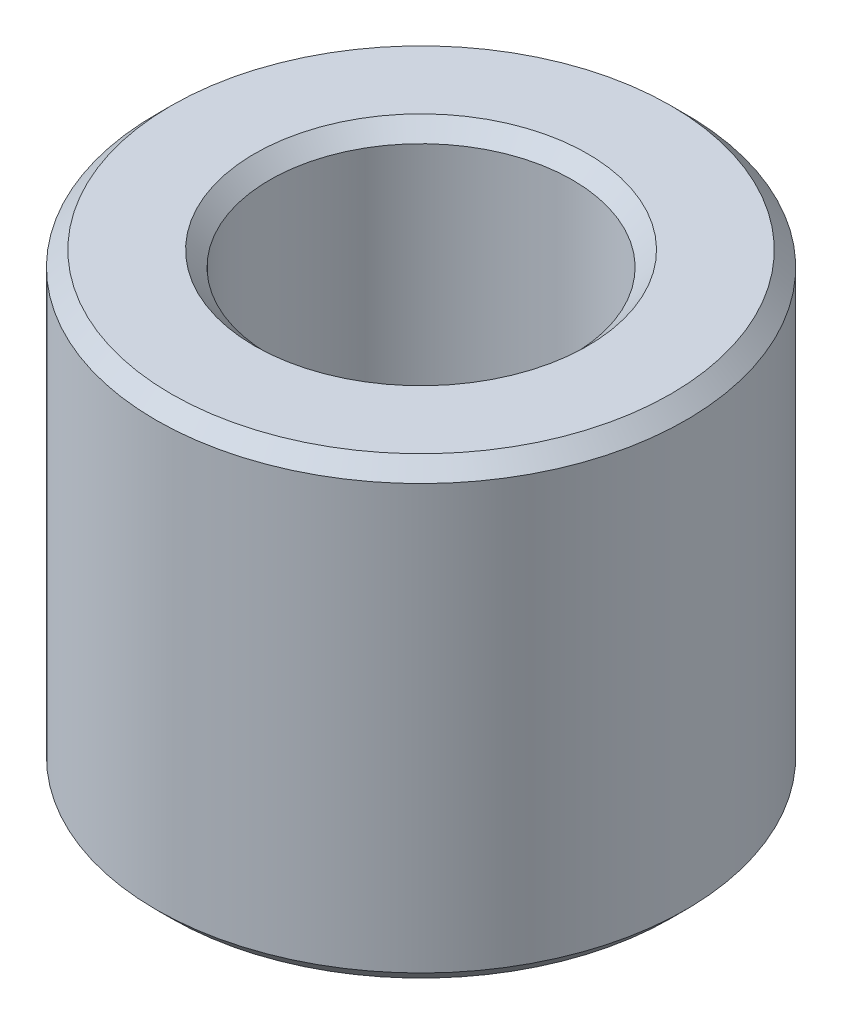
SolidWorks part; units mm, degrees
material "Stop 1060"
ref_plane "Płaszczyzna przednia" through (0, 0, 0) normal (0, 0, 1) x (1, 0, 0)
ref_plane "Płaszczyzna górna" through (0, 0, 0) normal (0, 1, 0) x (1, 0, 0)
ref_plane "Płaszczyzna prawa" through (0, 0, 0) normal (1, 0, 0) x (0, 0, -1)
sketch "Szkic1" plane through (0, 0, 0) normal (0, 1, 0) x (1, 0, 0)
  circle A0 centre (0, 0) radius 3.5
  circle A1 centre (0, 0) radius 2
  dimension "D1" = 7
  dimension "D2" = 4
extrude "Dodanie-wyciągnięcie1" add sketch "Szkic1" along normal blind 6
chamfer "Sfazowanie1" distance 0.2 angle 45 4 edges at (0, 0, 2) (0, 0, 3.5) (0, 6, 2) (0, 6, 3.5)
